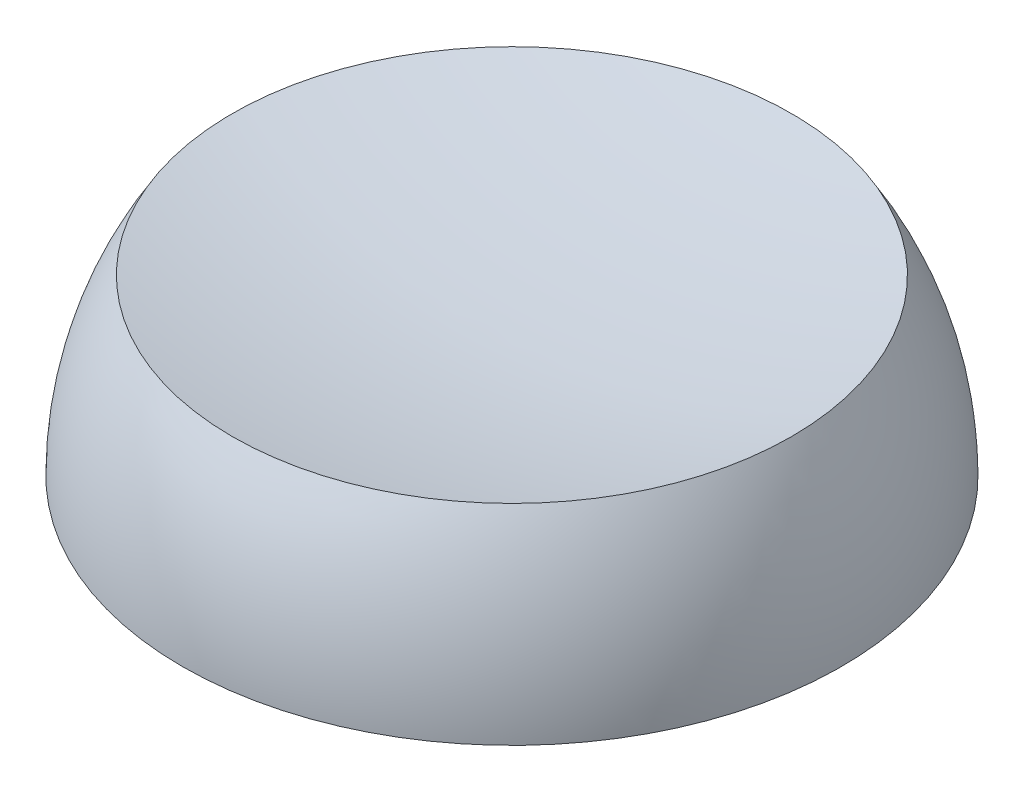
SolidWorks part; units mm, degrees
ref_plane "Front Plane" through (0, 0, 0) normal (0, 0, 1) x (1, 0, 0)
ref_plane "Top Plane" through (0, 0, 0) normal (0, 1, 0) x (1, 0, 0)
ref_plane "Right Plane" through (0, 0, 0) normal (1, 0, 0) x (0, 0, -1)
sketch "Sketch1" plane through (0, 0, 0) normal (0, 0, 1) x (1, 0, 0)
  line L0 (0, 11.0146) -> (0, 0) construction
  line L1 (0, 0) -> (10.7239, 0) construction
  line L3 (9, 0) -> (10, 0)
  line L4 (0, 4.301) -> (0, 3.301)
  arc A0 (10, 0) -> (8.4871, 5.2885) centre (0, 0) ccw
  arc A1 (9, 0) -> (7.9859, 4.1504) centre (0, 0) ccw
  arc A4 (0, 3.301) -> (7.9859, 4.1504) centre (0, 41.2658) ccw
  arc A5 (0, 4.301) -> (8.4871, 5.2885) centre (0, 41.2658) ccw
  dimension "D1" = 20
  dimension "D2" = 18
revolve "Revolve1" add sketch "Sketch1" angle 360 about L0
